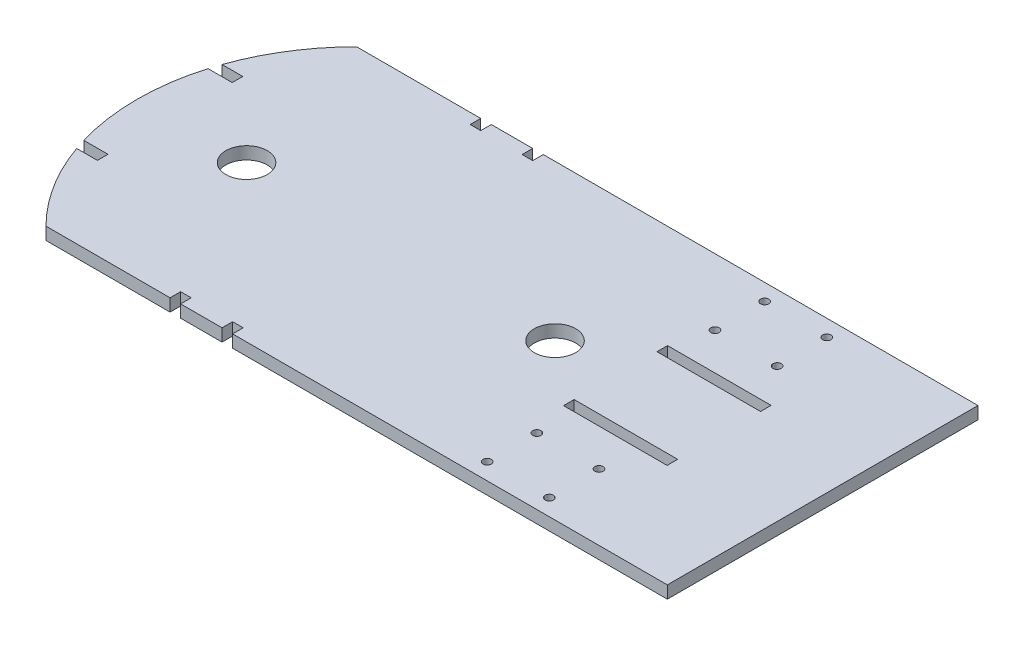
SolidWorks part; units mm, degrees
ref_plane "Front Plane" through (0, 0, 0) normal (0, 0, 1) x (1, 0, 0)
ref_plane "Top Plane" through (0, 0, 0) normal (0, 1, 0) x (1, 0, 0)
ref_plane "Right Plane" through (0, 0, 0) normal (1, 0, 0) x (0, 0, -1)
sketch "Sketch1" plane through (0, 0, 0) normal (0, 1, 0) x (1, 0, 0)
  line L0 (-37.5323, 97.8261) -> (-37.5323, -115.3533) construction
  line L1 (42.4677, -75) -> (-167.4323, -75)
  line L2 (42.4677, -75) -> (42.4677, 75)
  line L3 (42.4677, 75) -> (-167.4323, 75)
  line L5 (-57.5323, 97.8261) -> (-57.5323, -115.3533) construction
  line L6 (-17.5323, 97.8261) -> (-17.5323, -115.3533) construction
  line L7 (-149.4431, 35) -> (181.238, 35) construction
  line L8 (-149.4431, -35) -> (181.238, -35) construction
  line L9 (-316.5586, 0) -> (264.7652, 0) construction
  line L12 (-182.5323, 121.6083) -> (-182.5323, -145.4502) construction
  line L13 (-197.6323, 75) -> (-197.6323, 69.9)
  line L14 (-197.6323, 69.9) -> (-192.5323, 69.9)
  line L15 (-192.5323, 69.9) -> (-192.5323, 75)
  line L16 (-197.6323, 75) -> (-257.5323, 75)
  line L17 (-172.5323, 75) -> (-172.5323, 69.9)
  line L18 (-172.5323, 69.9) -> (-167.4323, 69.9)
  line L19 (-167.4323, 69.9) -> (-167.4323, 75)
  line L20 (-172.5323, 75) -> (-192.5323, 75)
  line L21 (-192.5323, -69.9) -> (-192.5323, -75)
  line L22 (-167.4323, -69.9) -> (-167.4323, -75)
  line L23 (-172.5323, -69.9) -> (-167.4323, -69.9)
  line L24 (-172.5323, -75) -> (-172.5323, -69.9)
  line L25 (-197.6323, -69.9) -> (-192.5323, -69.9)
  line L26 (-197.6323, -75) -> (-197.6323, -69.9)
  line L27 (-197.6323, -75) -> (-257.5323, -75)
  line L28 (-172.5323, -75) -> (-192.5323, -75)
  line L29 (-284.2672, 30) -> (-272.6222, 30)
  line L30 (-272.6222, 30) -> (-272.6222, 35.1)
  line L31 (-272.6222, 35.1) -> (-282.6222, 35.1)
  line L32 (-272.6222, -30) -> (-272.6222, -35.1)
  line L33 (-284.2672, -30) -> (-272.6222, -30)
  line L34 (-272.6222, -35.1) -> (-282.6222, -35.1)
  circle A0 centre (-52.5323, 67) radius 2
  circle A1 centre (-22.5323, 67) radius 2
  circle A2 centre (-22.5323, 43) radius 2
  circle A3 centre (-52.5323, 43) radius 2
  circle A4 centre (-22.5323, -67) radius 2
  circle A5 centre (-22.5323, -43) radius 2
  circle A6 centre (-52.5323, -43) radius 2
  circle A7 centre (-52.5323, -67) radius 2
  arc A8 (-257.5323, 75) -> (-282.6222, 35.1) centre (-182.5323, 0) ccw
  circle A9 centre (-86.7612, 0) radius 10
  circle A10 centre (-235.6922, 0) radius 10
  arc A11 (-284.2672, 30) -> (-284.2672, -30) centre (-182.5323, 0) ccw
  arc A12 (-282.6222, -35.1) -> (-257.5323, -75) centre (-182.5323, 0) ccw
  point P0 (0, 0)
  point P45 (-167.4323, 72.45)
  dimension "D8" = 4
  dimension "D13" = 106.066
  dimension "D21" = 20
  dimension "D22" = 20
  dimension "D1" = 150
  dimension "D2" = 60
  dimension "D3" = 75
  dimension "D4" = 40
  dimension "D5" = 40
  dimension "D6" = 40
  dimension "D7" = 20
  dimension "D9" = 30
  dimension "D10" = 5
  dimension "D11" = 8
  dimension "D12" = 24
  dimension "D14" = 5.1
  dimension "D15" = 5.1
  dimension "D16" = 5.1
  dimension "D17" = 5.1
  dimension "D18" = 10
  dimension "D19" = 10
  dimension "D20" = 300
  dimension "D23" = 5.1
  dimension "D24" = 10
  dimension "D25" = 30
extrude "Boss-Extrude1" add sketch "Sketch1" along normal blind 6
sketch "Sketch2" plane through (0, 6, 0) normal (0, 1, 0) x (1, 0, 0)
  line L0 (42.4677, -75) -> (42.4677, 75) construction
  line L1 (-57.5323, 25.1) -> (-7.5323, 25.1)
  line L2 (-57.5323, 25.1) -> (-57.5323, 20)
  line L3 (-57.5323, 20) -> (-7.5323, 20)
  line L4 (-7.5323, 25.1) -> (-7.5323, 20)
  line L5 (-57.5323, 25.1) -> (-7.5323, 20) construction
  line L6 (-57.5323, 20) -> (-7.5323, 25.1) construction
  line L7 (-57.5323, -20) -> (-7.5323, -20)
  line L8 (-57.5323, -20) -> (-57.5323, -25.1)
  line L9 (-57.5323, -25.1) -> (-7.5323, -25.1)
  line L10 (-7.5323, -20) -> (-7.5323, -25.1)
  line L11 (-57.5323, -20) -> (-7.5323, -25.1) construction
  line L12 (-57.5323, -25.1) -> (-7.5323, -20) construction
  point P0 (-32.5323, 22.55)
  point P5 (-32.5323, -22.55)
  dimension "D1" = 5.1
  dimension "D2" = 5.1
  dimension "D3" = 50
  dimension "D4" = 50
  dimension "D5" = 20
  dimension "D6" = 20
  dimension "D7" = 50
extrude "Cut-Extrude1" cut sketch "Sketch2" against normal through all
